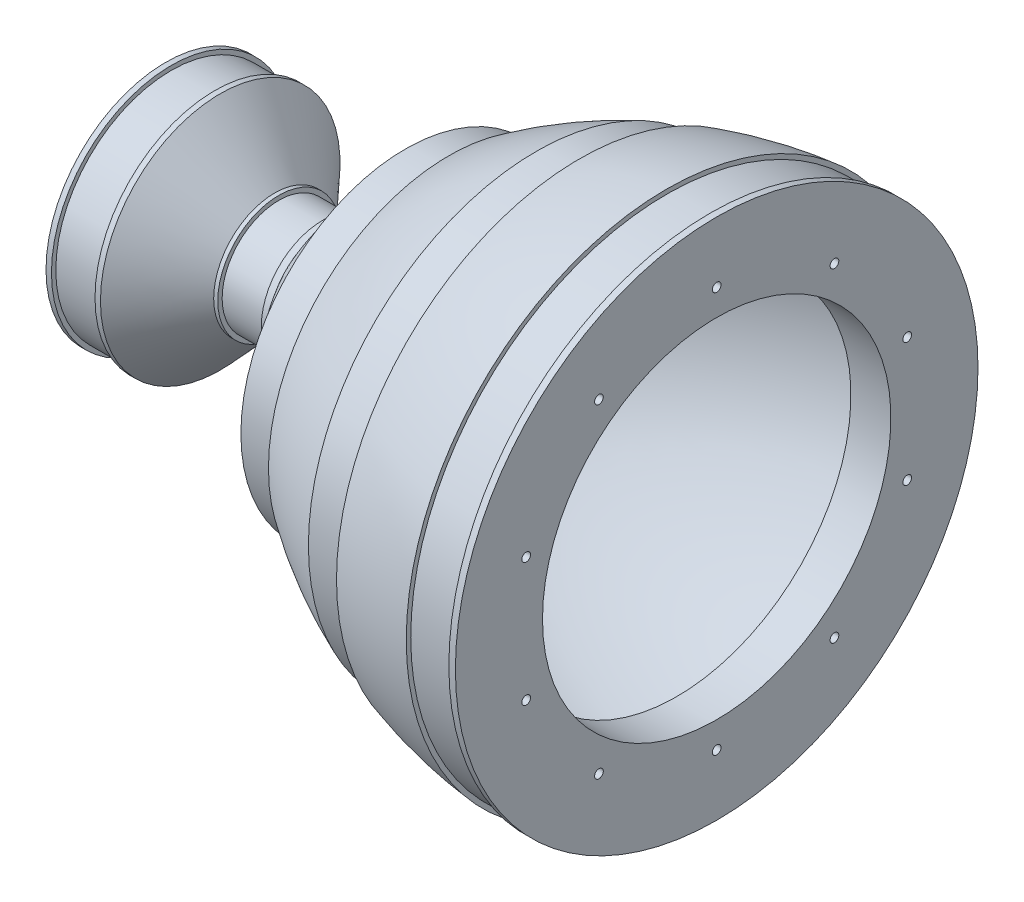
SolidWorks part; units mm, degrees
ref_plane "Front Plane" through (0, 0, 0) normal (0, 0, 1) x (1, 0, 0)
ref_plane "Top Plane" through (0, 0, 0) normal (0, 1, 0) x (1, 0, 0)
ref_plane "Right Plane" through (0, 0, 0) normal (1, 0, 0) x (0, 0, -1)
sketch "Sketch1" plane through (0, 0, 0) normal (0, 0, 1) x (1, 0, 0)
  line L0 (-6.2057, 80) -> (-24.5633, 80)
  line L1 (-24.5633, 80) -> (-24.5633, 110)
  line L2 (-6.2057, 80) -> (-6.2057, 120)
  line L3 (-184.2057, 28) -> (-187.3146, 28)
  line L4 (-178.2057, 20) -> (-213.0337, 20)
  line L5 (-209.2057, 28) -> (-234.2057, 55)
  line L6 (-234.2057, 55) -> (-236.7057, 55)
  line L7 (-259.2057, 55) -> (-259.2057, 30)
  line L8 (-259.2057, 30) -> (-249.2057, 30)
  line L9 (-249.2057, 30) -> (-249.2057, 48.2657)
  line L10 (-249.2057, 48.2657) -> (-239.2057, 48.2657)
  line L11 (-239.2057, 48.2657) -> (-213.0337, 20)
  line L12 (-6.2057, 120) -> (-9.2057, 120)
  line L13 (-9.2057, 120) -> (-9.2057, 117.5)
  line L14 (-9.2057, 117.5) -> (-29.2057, 117.5)
  line L15 (-29.2057, 117.5) -> (-29.2057, 119.5633)
  line L16 (-303.2348, 0) -> (142.8577, 0) construction
  line L17 (-129.2057, 82.8385) -> (-129.2057, 75.5)
  line L18 (-89.2057, 104.5) -> (-69.2057, 104.5)
  line L19 (-69.2057, 104.5) -> (-69.2057, 111.5964)
  line L20 (-129.2057, 75.5) -> (-149.2057, 75.5)
  line L21 (-149.2057, 75.5) -> (-149.2057, 67.2754)
  line L22 (-207.3146, 28) -> (-209.2057, 28)
  line L24 (-207.3146, 28) -> (-207.3146, 26)
  line L25 (-207.3146, 26) -> (-187.3146, 26)
  line L26 (-187.3146, 28) -> (-187.3146, 26)
  line L27 (-256.7057, 55) -> (-259.2057, 55)
  line L29 (-256.7057, 55) -> (-256.7057, 53)
  line L30 (-256.7057, 53) -> (-236.7057, 53)
  line L31 (-236.7057, 55) -> (-236.7057, 53)
  arc A2 (-178.2057, 20) -> (-24.5633, 110) centre (-8.0506, -94.3339) cw
  arc A3 (-29.2057, 119.5633) -> (-69.2057, 111.5964) centre (-7.3982, -94.3279) ccw
  arc A4 (-89.2057, 104.5) -> (-129.2057, 82.8385) centre (-7.3982, -94.3279) ccw
  arc A5 (-149.2057, 67.2754) -> (-184.2057, 28) centre (-7.3982, -94.3279) ccw
  dimension "D1" = 8
  dimension "D9" = 20
  dimension "D10" = 205
  dimension "D2" = 10
  dimension "D3" = 10
  dimension "D4" = 25
  dimension "D5" = 25
  dimension "D6" = 20
  dimension "D7" = 55
  dimension "D8" = 120
  dimension "D11" = 253
  dimension "D12" = 80
  dimension "D13" = 3
  dimension "D14" = 2.5
  dimension "D15" = 10
  dimension "D16" = 63
  dimension "D17" = 20
  dimension "D18" = 10
  dimension "D19" = 104.5
  dimension "D20" = 25
  dimension "D21" = 20
  dimension "D22" = 75.5
  dimension "D23" = 40
  dimension "D24" = 20
  dimension "D25" = 2
  dimension "D26" = 20
  dimension "D27" = 2
  dimension "D28" = 25
  dimension "D29" = 2.5
revolve "Revolve3" add sketch "Sketch1" angle 360 about L16
sketch "Sketch3" plane through (-6.2057, 0, 0) normal (1, 0, 0) x (0, 0, -1)
  circle A0 centre (0, 92) radius 2
  circle A1 centre (54.0762, 74.4296) radius 2
  circle A2 centre (87.4972, 28.4296) radius 2
  circle A3 centre (87.4972, -28.4296) radius 2
  circle A4 centre (54.0762, -74.4296) radius 2
  circle A5 centre (0, -92) radius 2
  circle A6 centre (-54.0762, -74.4296) radius 2
  circle A7 centre (-87.4972, -28.4296) radius 2
  circle A8 centre (-87.4972, 28.4296) radius 2
  circle A9 centre (-54.0762, 74.4296) radius 2
  point P24 (0, 0)
  dimension "D1" = 92
  dimension "D2" = 10
extrude "Cut-Extrude1" cut sketch "Sketch3" against normal blind 10
sketch "Sketch4" plane through (-259.2057, 0, 0) normal (-1, 0, 0) x (0, 0, 1)
  circle A0 centre (0, 47.5) radius 2
  circle A1 centre (27.9198, 38.4283) radius 2
  circle A2 centre (45.1752, 14.6783) radius 2
  circle A3 centre (45.1752, -14.6783) radius 2
  circle A4 centre (27.9198, -38.4283) radius 2
  circle A5 centre (0, -47.5) radius 2
  circle A6 centre (-27.9198, -38.4283) radius 2
  circle A7 centre (-45.1752, -14.6783) radius 2
  circle A8 centre (-45.1752, 14.6783) radius 2
  circle A9 centre (-27.9198, 38.4283) radius 2
  point P23 (0, 0)
  dimension "D1" = 47.5
  dimension "D2" = 10
extrude "Cut-Extrude2" cut sketch "Sketch4" against normal blind 10
